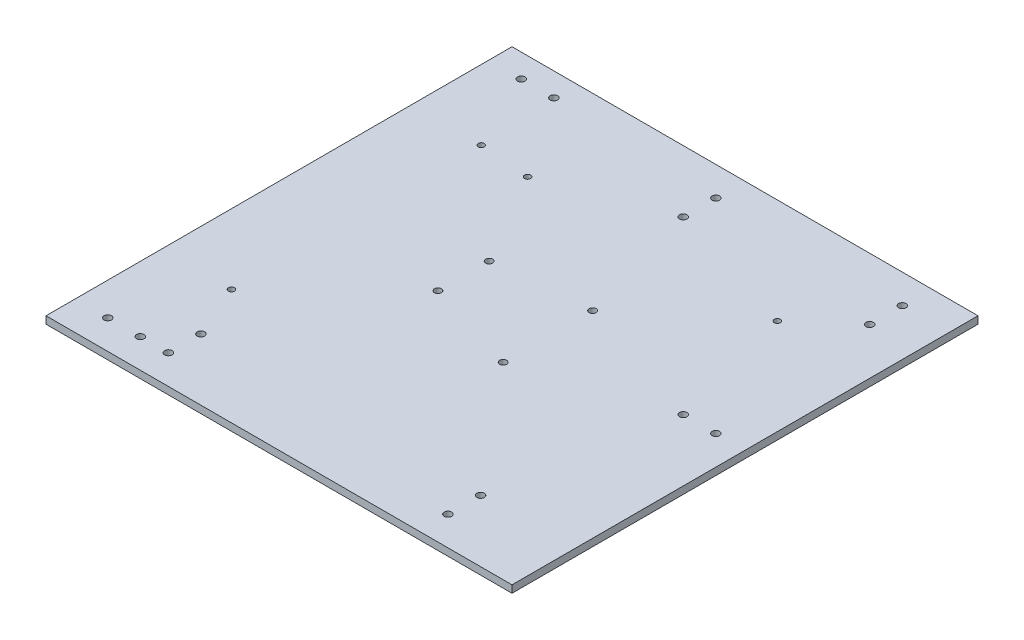
SolidWorks part; units mm, degrees
ref_plane "Front Plane" through (0, 0, 0) normal (0, 0, 1) x (1, 0, 0)
ref_plane "Top Plane" through (0, 0, 0) normal (0, 1, 0) x (1, 0, 0)
ref_plane "Right Plane" through (0, 0, 0) normal (1, 0, 0) x (0, 0, -1)
sketch "Sketch1" plane through (0, 0, 0) normal (0, 1, 0) x (1, 0, 0)
  line L0 (0, 0) -> (254, 0)
  line L1 (254, 0) -> (254, 254)
  line L2 (254, 254) -> (0, 254)
  line L3 (0, 254) -> (0, 0)
  line L4 (0, 127) -> (127, 127) construction
  line L5 (127, 127) -> (127, 100.33) construction
  line L6 (127, 127) -> (127, 153.67) construction
  line L7 (127, 153.67) -> (92.71, 153.67) construction
  line L8 (127, 153.67) -> (161.29, 153.67) construction
  line L9 (92.71, 153.67) -> (92.71, 146.558) construction
  line L10 (161.29, 100.33) -> (146.558, 100.33) construction
  line L11 (161.29, 100.33) -> (161.29, 153.67) construction
  line L12 (92.71, 146.558) -> (94.996, 146.558) construction
  line L13 (94.996, 146.558) -> (94.996, 118.618) construction
  line L14 (92.71, 146.558) -> (92.71, 100.33) construction
  line L15 (146.558, 100.33) -> (146.558, 102.616) construction
  line L16 (146.558, 153.67) -> (146.558, 151.384) construction
  line L17 (92.71, 100.33) -> (146.558, 100.33) construction
  line L18 (38.1, 65.278) -> (38.1, 62.992) construction
  line L19 (50.8, 15.875) -> (35.56, 15.875) construction
  line L20 (0, 254) -> (38.1, 254) construction
  line L21 (35.56, 15.875) -> (17.78, 15.875) construction
  line L22 (38.1, 196.85) -> (48.895, 196.85) construction
  line L23 (38.1, 196.85) -> (27.305, 196.85) construction
  line L24 (27.305, 196.85) -> (27.305, 65.278) construction
  line L25 (27.305, 65.278) -> (48.895, 65.278) construction
  line L26 (48.895, 65.278) -> (48.895, 196.85) construction
  line L27 (228.6, 238.125) -> (127, 238.125) construction
  line L28 (67.945, 196.85) -> (67.945, 207.645) construction
  line L29 (67.945, 196.85) -> (67.945, 186.055) construction
  line L30 (67.945, 207.645) -> (199.517, 207.645) construction
  line L31 (67.945, 186.055) -> (199.517, 186.055) construction
  line L32 (199.517, 186.055) -> (199.517, 207.645) construction
  line L33 (38.1, 196.85) -> (38.1, 199.136) construction
  line L34 (67.945, 196.85) -> (65.659, 196.85) construction
  line L35 (199.517, 196.85) -> (201.803, 196.85) construction
  line L36 (246.761, 127) -> (246.761, 133.604) construction
  line L37 (246.761, 133.604) -> (210.693, 133.604) construction
  line L38 (210.693, 133.604) -> (210.693, 120.396) construction
  line L39 (210.693, 120.396) -> (246.761, 120.396) construction
  line L40 (246.761, 120.396) -> (246.761, 127) construction
  line L41 (210.693, 127) -> (220.345, 127) construction
  line L42 (220.345, 127) -> (238.125, 127) construction
  line L43 (0, 0) -> (50.8, 0) construction
  line L44 (127, 254) -> (127, 238.125) construction
  line L45 (50.8, 7.239) -> (57.404, 7.239) construction
  line L46 (57.404, 7.239) -> (57.404, 43.307) construction
  line L47 (57.404, 43.307) -> (44.196, 43.307) construction
  line L48 (44.196, 43.307) -> (44.196, 7.239) construction
  line L49 (44.196, 7.239) -> (50.8, 7.239) construction
  line L50 (50.8, 43.307) -> (50.8, 33.655) construction
  line L51 (50.8, 33.655) -> (50.8, 15.875) construction
  line L52 (254, 254) -> (228.6, 254) construction
  line L53 (228.6, 220.345) -> (127, 220.345) construction
  line L54 (228.6, 246.761) -> (235.204, 246.761) construction
  line L55 (235.204, 246.761) -> (235.204, 210.693) construction
  line L56 (235.204, 210.693) -> (221.996, 210.693) construction
  line L57 (221.996, 210.693) -> (221.996, 246.761) construction
  line L58 (221.996, 246.761) -> (228.6, 246.761) construction
  line L59 (228.6, 210.693) -> (228.6, 220.345) construction
  line L60 (228.6, 220.345) -> (228.6, 238.125) construction
  line L61 (17.78, 241.2768) -> (17.78, 254) construction
  line L62 (17.78, 241.2768) -> (35.56, 241.2768) construction
  circle A4 centre (201.803, 196.85) radius 1.651
  circle A5 centre (65.659, 196.85) radius 1.651
  circle A6 centre (38.1, 199.136) radius 1.651
  circle A8 centre (220.345, 127) radius 2.032
  circle A9 centre (238.125, 127) radius 2.032
  circle A10 centre (50.8, 33.655) radius 2.032
  circle A11 centre (50.8, 15.875) radius 2.032
  circle A12 centre (228.6, 238.125) radius 2.032
  circle A13 centre (228.6, 220.345) radius 2.032
  circle A14 centre (94.996, 146.558) radius 1.905
  circle A15 centre (94.996, 118.618) radius 1.905
  circle A16 centre (146.558, 102.616) radius 1.905
  circle A17 centre (146.558, 151.384) radius 1.905
  circle A18 centre (38.1, 62.992) radius 1.651
  circle A19 centre (203.2, 33.655) radius 2.032
  circle A20 centre (203.2, 15.875) radius 2.032
  circle A23 centre (127, 238.125) radius 2.032
  circle A24 centre (127, 220.345) radius 2.032
  circle A25 centre (35.56, 15.875) radius 2.032
  circle A26 centre (17.78, 15.875) radius 2.032
  circle A27 centre (17.78, 241.2768) radius 2.032
  circle A28 centre (35.56, 241.2768) radius 2.032
  dimension "D4" = 68.58
  dimension "D7" = 27.94
  dimension "D14" = 3.302
  dimension "D22" = 9.652
  dimension "D27" = 36.068
  dimension "D33" = 15.875
  dimension "D18" = 50.8
  dimension "D37" = 15.875
  dimension "D38" = 15.24
  dimension "D39" = 17.78
  dimension "D1" = 254
  dimension "D2" = 254
  dimension "D5" = 53.34
  dimension "D6" = 2.286
  dimension "D8" = 7.112
  dimension "D9" = 131.572
  dimension "D10" = 21.59
  dimension "D11" = 57.15
  dimension "D12" = 38.1
  dimension "D13" = 19.05
  dimension "D15" = 131.572
  dimension "D16" = 2.286
  dimension "D17" = 2.286
  dimension "D19" = 36.068
  dimension "D20" = 13.208
  dimension "D21" = 9.652
  dimension "D23" = 36.068
  dimension "D24" = 13.208
  dimension "D25" = 50.8
  dimension "D26" = 17.78
  dimension "D28" = 25.4
  dimension "D29" = 15.875
  dimension "D30" = 13.208
  dimension "D31" = 9.652
  dimension "D32" = 17.78
  dimension "D34" = 15.875
  dimension "D35" = 17.78
  dimension "D36" = 17.78
extrude "Boss-Extrude1" add sketch "Sketch1" along normal blind 4
